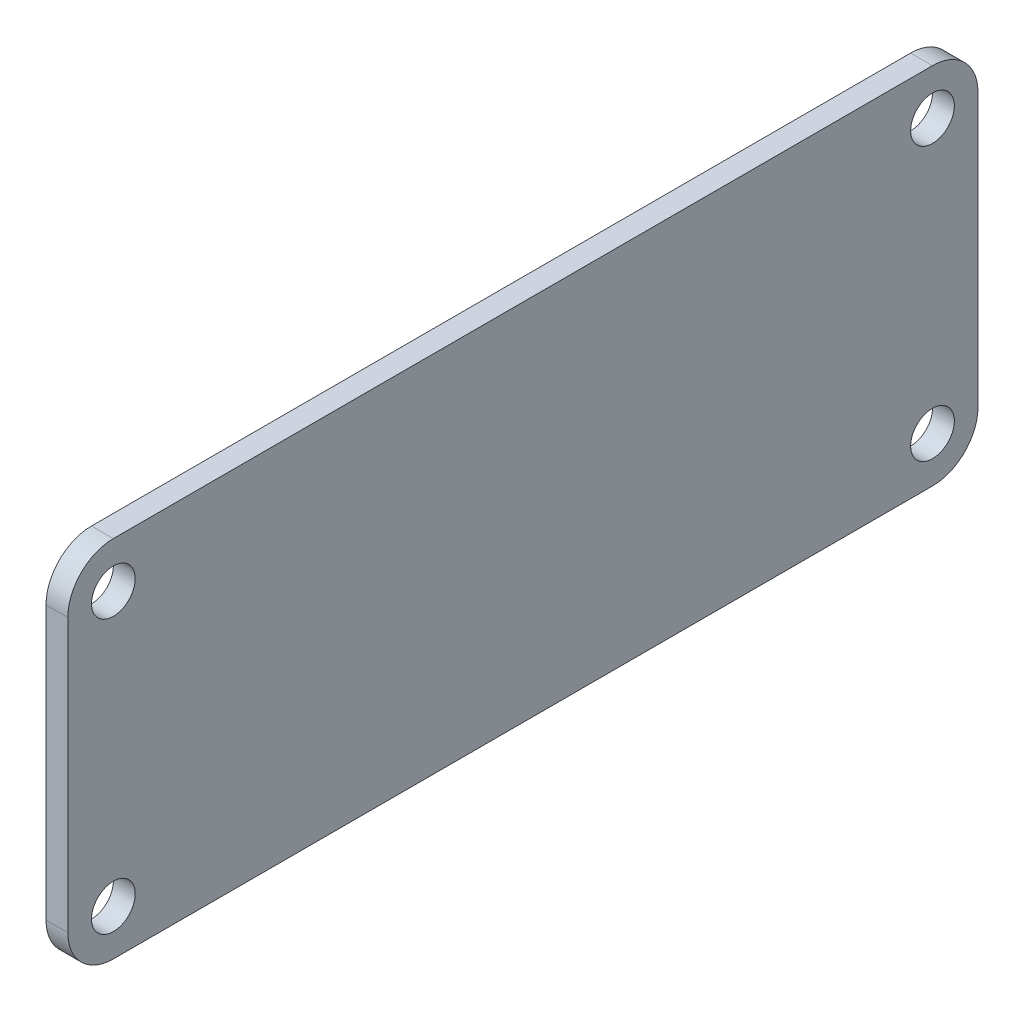
SolidWorks part; units mm, degrees
ref_plane "Front Plane" through (0, 0, 0) normal (0, 0, 1) x (1, 0, 0)
ref_plane "Top Plane" through (0, 0, 0) normal (0, 1, 0) x (1, 0, 0)
ref_plane "Right Plane" through (0, 0, 0) normal (1, 0, 0) x (0, 0, -1)
sketch "Sketch2" plane through (0, 0, 0) normal (1, 0, 0) x (0, 0, -1)
  line L1 (-28.575, -12.7) -> (28.575, -12.7)
  line L2 (-31.75, -9.525) -> (-31.75, 9.525)
  line L3 (-28.575, 12.7) -> (28.575, 12.7)
  line L4 (31.75, -9.525) -> (31.75, 9.525)
  line L5 (-31.75, -12.7) -> (31.75, 12.7) construction
  line L6 (-31.75, 12.7) -> (31.75, -12.7) construction
  circle A0 centre (-28.575, 9.525) radius 1.524
  circle A1 centre (28.575, 9.525) radius 1.524
  circle A2 centre (28.575, -9.525) radius 1.524
  circle A3 centre (-28.575, -9.525) radius 1.524
  arc A4 (-28.575, -12.7) -> (-31.75, -9.525) centre (-28.575, -9.525) cw
  arc A5 (28.575, -12.7) -> (31.75, -9.525) centre (28.575, -9.525) ccw
  arc A6 (28.575, 12.7) -> (31.75, 9.525) centre (28.575, 9.525) cw
  arc A7 (-31.75, 9.525) -> (-28.575, 12.7) centre (-28.575, 9.525) cw
  point P0 (0, 0)
  dimension "D7" = 3.048
  dimension "D8" = 3.175
  dimension "D1" = 25.4
  dimension "D2" = 63.5
  dimension "D3" = 3.175
  dimension "D4" = 3.175
  dimension "D5" = 3.175
  dimension "D6" = 3.175
extrude "Boss-Extrude1" add sketch "Sketch2" along normal blind 1.524
